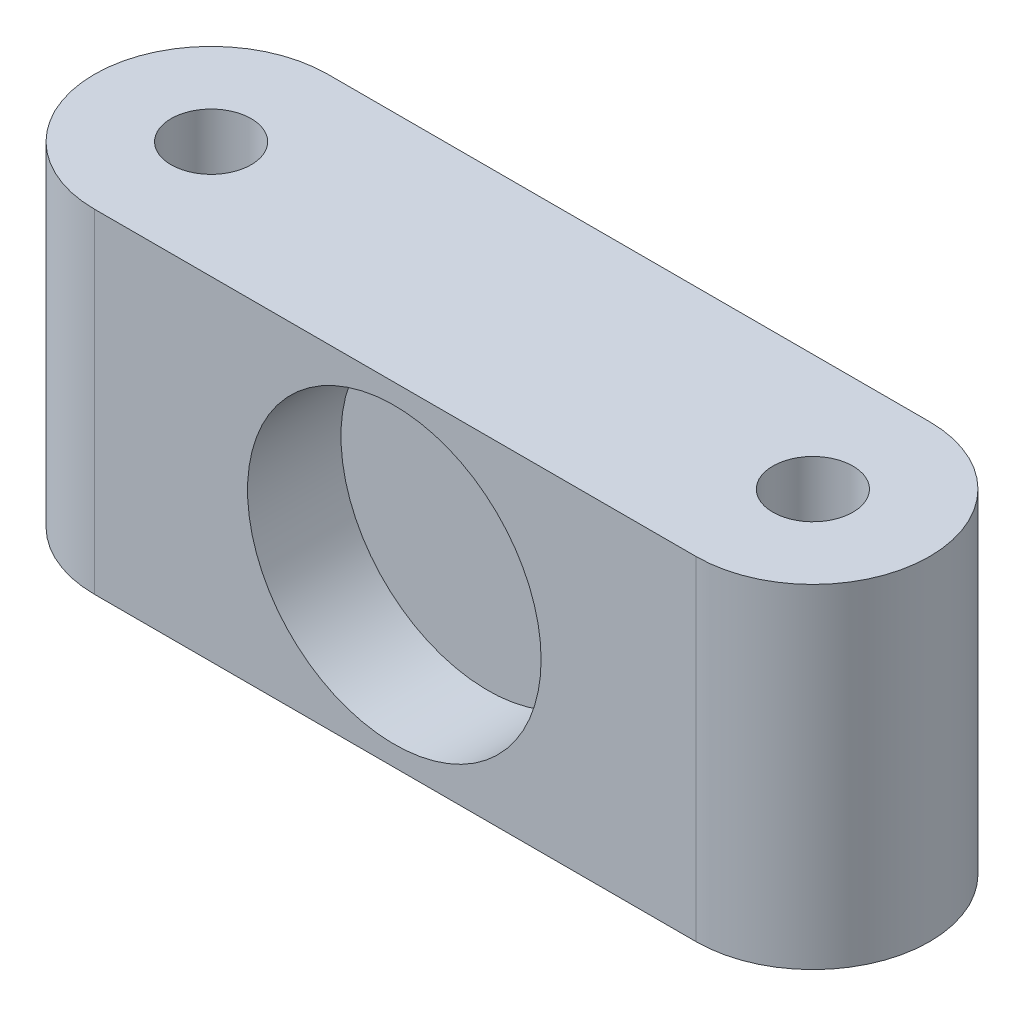
SolidWorks part; units mm, degrees
ref_plane "Front Plane" through (0, 0, 0) normal (0, 0, 1) x (1, 0, 0)
ref_plane "Top Plane" through (0, 0, 0) normal (0, 1, 0) x (1, 0, 0)
ref_plane "Right Plane" through (0, 0, 0) normal (1, 0, 0) x (0, 0, -1)
sketch "Sketch1" plane through (0, 0, 0) normal (0, 1, 0) x (1, 0, 0)
  line L0 (-22.4807, -8.9687) -> (22.6193, -8.9687)
  line L2 (-22.4807, 8.5313) -> (22.6193, 8.5313)
  arc A0 (-22.4807, 8.5313) -> (-22.4807, -8.9687) centre (-22.4807, -0.2187) ccw
  arc A1 (22.6193, -8.9687) -> (22.6193, 8.5313) centre (22.6193, -0.2187) ccw
  circle A2 centre (-22.4807, -0.2187) radius 3
  circle A3 centre (22.6193, -0.2187) radius 3
  dimension "D3" = 6
  dimension "D4" = 6
  dimension "D1" = 8.75
  dimension "D2" = 8.75
extrude "Boss-Extrude1" add sketch "Sketch1" along normal blind 25
sketch "Sketch3" plane through (0, 0, 8.9687) normal (0, 0, 1) x (1, 0, 0)
  circle A0 centre (0, 12.5) radius 11
  point P2 (0, 0)
  dimension "D1" = 12.5
extrude "Cut-Extrude1" cut sketch "Sketch3" against normal blind 7
sketch3d "3DSketch2" plane through (0, 0, 0) normal (0, 0, 1) x (1, 0, 0)
  dimension "D1" = 9.8
sketch "Sketch4" plane through (0, 9.8, 0) normal (0, 1, 0) x (1, 0, 0)
  line L1 (-20.7307, 2.218) -> (-20.7307, 1.5313)
  line L2 (-24.2307, 2.218) -> (-24.2307, 1.5313)
  line L3 (-22.4807, 3.4361) -> (-22.4807, -2.5639) construction
  line L4 (-24.9174, 1.5313) -> (-24.2307, 1.5313)
  line L5 (-19.4807, -0.2187) -> (-20.7307, -0.2187) construction
  line L6 (-24.9174, -1.9687) -> (-24.2307, -1.9687)
  line L7 (-24.2307, -1.9687) -> (-24.2307, -2.6554)
  line L8 (-20.7307, 1.5313) -> (-20.044, 1.5313)
  line L9 (-20.7307, -1.9687) -> (-20.7307, -2.6554)
  line L10 (-22.4807, -0.2187) -> (-25.4807, -0.2187) construction
  line L11 (-20.7307, -1.9687) -> (-20.044, -1.9687)
  arc A1 (-24.9174, 1.5313) -> (-24.9174, -1.9687) centre (-22.4807, -0.2187) ccw
  arc A2 (-20.7307, 2.218) -> (-24.2307, 2.218) centre (-22.4807, -0.2187) ccw
  arc A3 (-24.2307, -2.6554) -> (-20.7307, -2.6554) centre (-22.4807, -0.2187) ccw
  arc A4 (-20.044, -1.9687) -> (-20.044, 1.5313) centre (-22.4807, -0.2187) ccw
  point P23 (0, 0)
  point P24 (0, 0)
  dimension "D1" = 1.75
  dimension "D2" = 1.75
  dimension "D3" = 1.75
  dimension "D4" = 1.75
extrude "Boss-Extrude2" add sketch "Sketch4" against normal blind 1.5
sketch "Sketch5" plane through (0, 9.8, 0) normal (0, 1, 0) x (1, 0, 0)
  line L1 (24.3693, 2.218) -> (24.3693, 1.5313)
  line L2 (20.8693, 2.218) -> (20.8693, 1.5313)
  line L3 (22.6193, 4.871) -> (22.6193, -1.129) construction
  line L4 (20.1826, 1.5313) -> (20.8693, 1.5313)
  line L5 (25.6193, -0.2187) -> (24.3693, -0.2187) construction
  line L6 (20.1826, -1.9687) -> (20.8693, -1.9687)
  line L7 (20.8693, -1.9687) -> (20.8693, -2.6554)
  line L8 (24.3693, 1.5313) -> (25.056, 1.5313)
  line L9 (24.3693, -1.9687) -> (24.3693, -2.6554)
  line L10 (22.6193, -0.2187) -> (19.6193, -0.2187) construction
  line L11 (24.3693, -1.9687) -> (25.056, -1.9687)
  arc A1 (20.1826, 1.5313) -> (20.1826, -1.9687) centre (22.6193, -0.2187) ccw
  arc A2 (24.3693, 2.218) -> (20.8693, 2.218) centre (22.6193, -0.2187) ccw
  arc A3 (20.8693, -2.6554) -> (24.3693, -2.6554) centre (22.6193, -0.2187) ccw
  arc A4 (25.056, -1.9687) -> (25.056, 1.5313) centre (22.6193, -0.2187) ccw
  dimension "D1" = 1.75
  dimension "D2" = 1.75
  dimension "D3" = 1.75
  dimension "D4" = 1.75
extrude "Boss-Extrude3" add sketch "Sketch5" against normal blind 1.5
